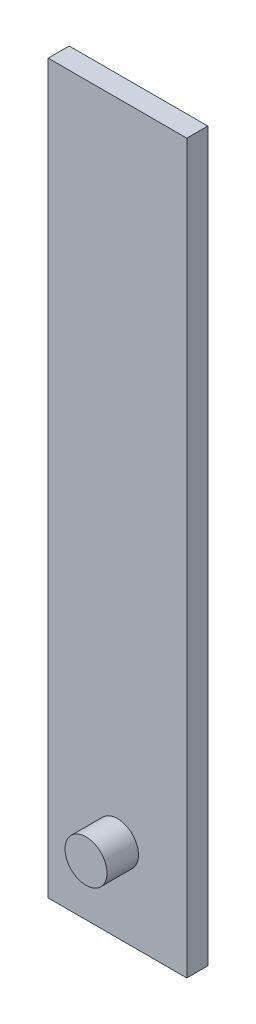
SolidWorks part; units mm, degrees
ref_plane "前视基准面" through (0, 0, 0) normal (0, 0, 1) x (1, 0, 0)
ref_plane "上视基准面" through (0, 0, 0) normal (0, 1, 0) x (1, 0, 0)
ref_plane "右视基准面" through (0, 0, 0) normal (1, 0, 0) x (0, 0, -1)
other "Configuration Table"
sketch "草图1" plane through (0, 0, 0) normal (0, 0, 1) x (1, 0, 0)
  line L1 (-6.5998, -34.6382) -> (6.5998, -34.6382)
  line L2 (-6.5998, -34.6382) -> (-6.5998, 34.6382)
  line L3 (-6.5998, 34.6382) -> (6.5998, 34.6382)
  line L4 (6.5998, -34.6382) -> (6.5998, 34.6382)
  line L5 (-6.5998, -34.6382) -> (6.5998, 34.6382) construction
  line L6 (-6.5998, 34.6382) -> (6.5998, -34.6382) construction
  point P0 (0, 0)
extrude "凸台-拉伸1" add sketch "草图1" along normal blind 2
sketch "草图2" plane through (0, 0, 2) normal (0, 0, 1) x (1, 0, 0)
  line L0 (0, -34.6382) -> (0, 34.6382) construction
  line L1 (-6.5998, -34.6382) -> (6.5998, -34.6382) construction
  line L2 (6.5998, 34.6382) -> (-6.5998, 34.6382) construction
  circle A0 centre (0, -26.7904) radius 2.0006
extrude "凸台-拉伸2" add sketch "草图2" along normal blind 3 and the other way blind 5
